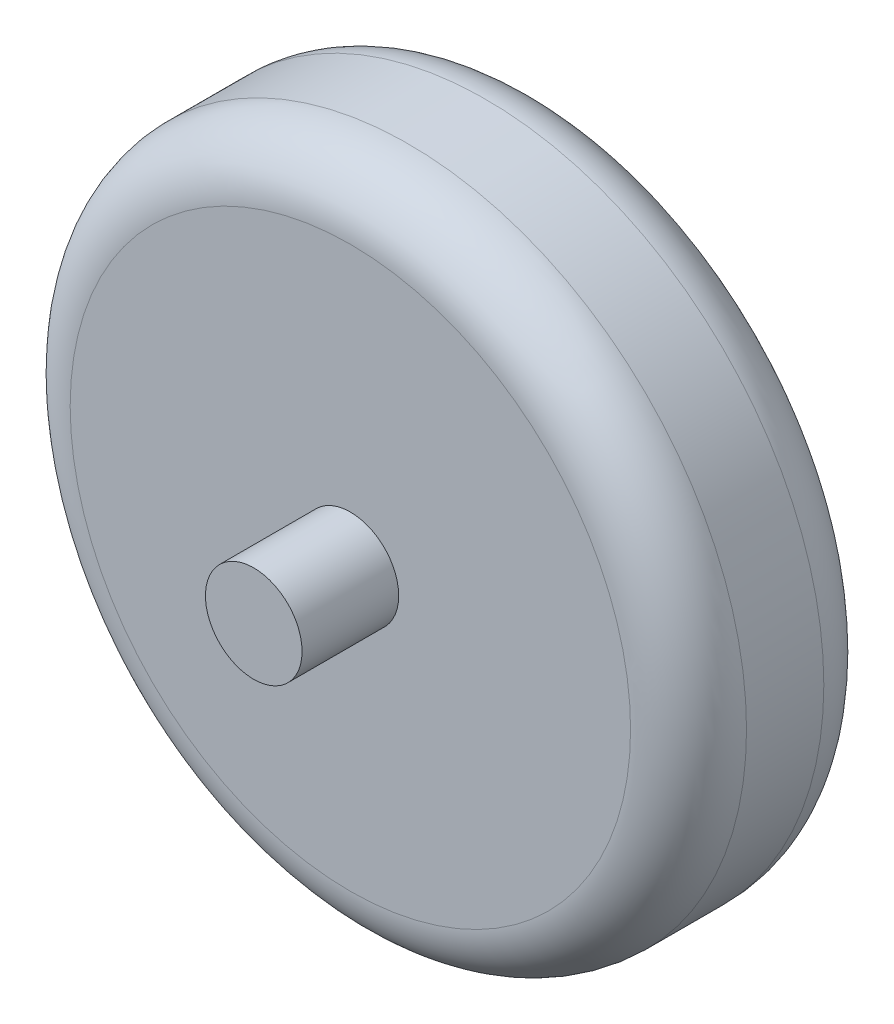
SolidWorks part; units mm, degrees
ref_plane "Front Plane" through (0, 0, 0) normal (0, 0, 1) x (1, 0, 0)
ref_plane "Top Plane" through (0, 0, 0) normal (0, 1, 0) x (1, 0, 0)
ref_plane "Right Plane" through (0, 0, 0) normal (1, 0, 0) x (0, 0, -1)
sketch "Sketch1" plane through (0, 0, 0) normal (0, 0, 1) x (1, 0, 0)
  circle A0 centre (0, 0) radius 17.5
  dimension "D1" = 35
extrude "Boss-Extrude1" add sketch "Sketch1" along normal mid plane 10
fillet "Fillet1" radius 3 2 edges at (17.5, 0, -5) (17.5, 0, 5)
sketch "Sketch2" plane through (0, 0, 0) normal (0, 0, 1) x (1, 0, 0)
  circle A0 centre (0, 0) radius 2.5
  dimension "D1" = 5
extrude "Boss-Extrude2" add sketch "Sketch2" along normal mid plane 20
